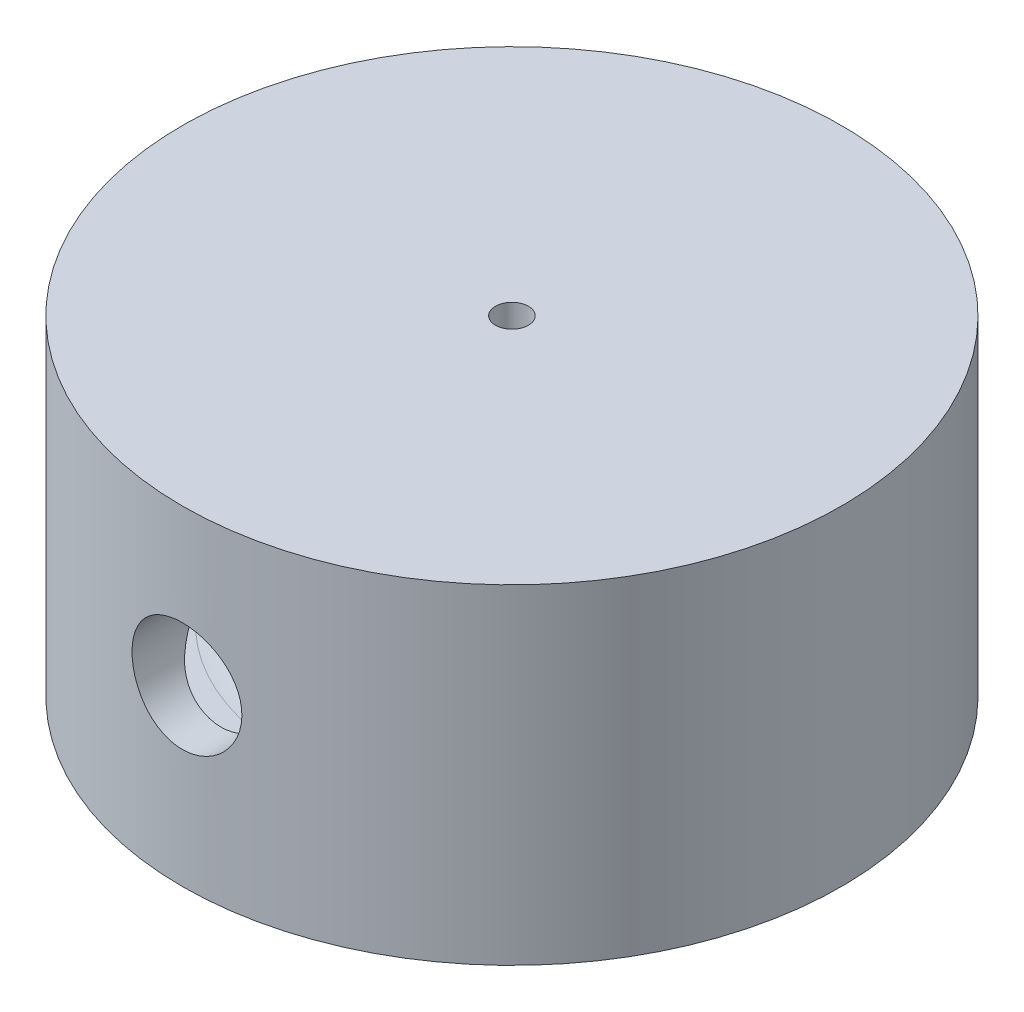
SolidWorks part; units mm, degrees
ref_plane "Front Plane" through (0, 0, 0) normal (0, 0, 1) x (1, 0, 0)
ref_plane "Top Plane" through (0, 0, 0) normal (0, 1, 0) x (1, 0, 0)
ref_plane "Right Plane" through (0, 0, 0) normal (1, 0, 0) x (0, 0, -1)
sketch "Sketch2" plane through (0, 0, 0) normal (0, 0, 1) x (1, 0, 0)
  line L0 (0, 28.7804) -> (0, -27.9337) construction
  line L1 (-36.96, 0.0952) -> (1.5, 0.0952) construction
  line L2 (0, 0.4233) -> (0.75, 0.0952) construction
  line L3 (0.75, 0.0952) -> (0.75, 15.0952)
  line L4 (0.75, 15.0952) -> (15, 15.0952)
  line L5 (15, 15.0952) -> (15, 0.0952)
  line L6 (15, 0.0952) -> (3.25, 0.0952)
  line L7 (0.75, 0.0952) -> (1.5, 0.0952) construction
  line L8 (1.5, 0.0952) -> (1.5, 12.781)
  line L15 (11.307, 2.9209) -> (10.1879, 2.9209)
  line L16 (5.2125, 9.1417) -> (5.414, 10.0359)
  line L17 (5.236, 9.2458) -> (5.0264, 8.3156)
  line L23 (3.25, 0.0952) -> (50.7531, 0.0952) construction
  line L24 (1.5, 0.0952) -> (0.75, 0.0952)
  line L27 (5.236, 9.2458) -> (5.414, 10.0359)
  line L28 (3.25, 11.9898) -> (3.25, 0.0952)
  line L30 (5.414, 10.0359) -> (3.25, 11.9898) construction
  line L32 (3.25, 13.9104) -> (4.2696, 13.9104)
  line L33 (8.5021, 12.9705) -> (8.5893, 12.9298)
  line L36 (10.9047, 10.8775) -> (12.8473, 6.906)
  line L37 (13.2542, 5.1484) -> (13.2542, 4.9209)
  line L39 (11.2542, 2.9209) -> (11.307, 2.9209)
  arc A2 (10.1879, 2.9209) -> (5.2125, 9.1417) centre (10.1879, 8.0209) cw
  arc A7 (3.25, 11.9898) -> (5.414, 10.0359) centre (4.332, 11.0129) cw
  arc A9 (1.5, 12.781) -> (3.25, 13.9104) centre (3.25, 11.9898) cw
  arc A10 (8.5021, 12.9705) -> (4.2696, 13.9104) centre (4.2696, 3.9104) ccw
  arc A11 (8.8859, 12.797) -> (8.5893, 12.9298) centre (12.8219, 21.9898) cw
  arc A12 (10.9047, 10.8775) -> (8.8859, 12.797) centre (7.3115, 9.1199) ccw
  arc A13 (12.8473, 6.906) -> (13.2542, 5.1484) centre (9.2542, 5.1484) cw
  arc A14 (11.2542, 2.9209) -> (13.2542, 4.9209) centre (11.2542, 4.9209) ccw
  point P34 (0, 0)
  point P35 (11.307, 2.9209)
  point P42 (5.2348, 9.2405)
  dimension "D7" = 1.1848
  dimension "D9" = 5.1
  dimension "D11" = 2
  dimension "D14" = 15
  dimension "D2" = 15
  dimension "D3" = 15
  dimension "D4" = 1.75
  dimension "D5" = 0.75
  dimension "D6" = 0.75
revolve "Revolve1" add sketch "Sketch2" angle 360 about L0
sketch3d "3DSketch1"
  circle A0 centre (-0.0074, 5.9778, 15) radius 2.25
  point P2 (-0.0074, 5.9778, 17.25)
  point P3 (0, 0, 0)
sketch "Sketch3" plane through (0, 0, 0) normal (0, 0, 1) x (1, 0, 0)
  circle A0 centre (0, 8) radius 2.5
  point P2 (0, 0)
  dimension "D1" = 5
  dimension "D2" = 8
extrude "Cut-Extrude2" cut sketch "Sketch3" along normal through all from offset 8
